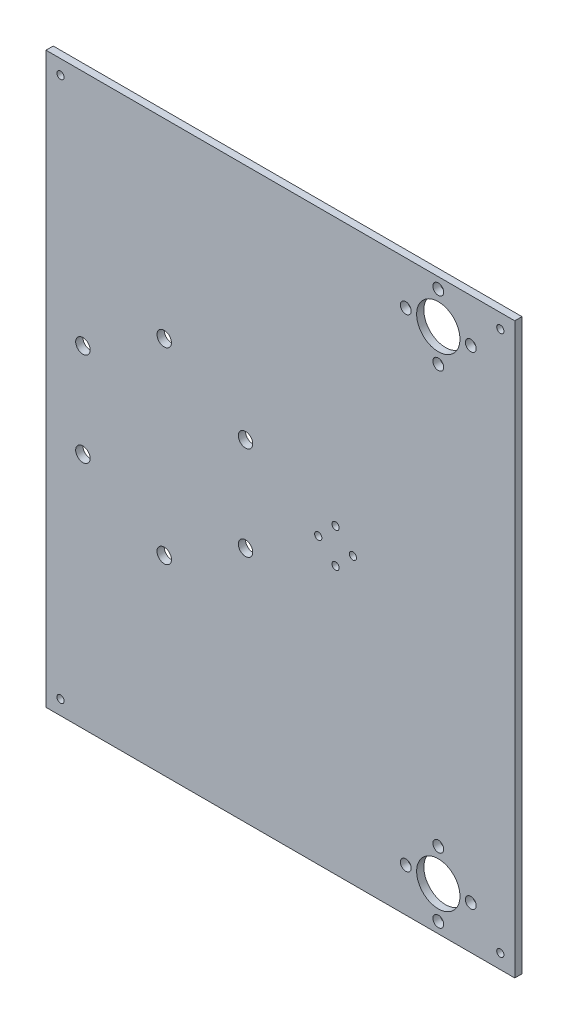
SolidWorks part; units mm, degrees
ref_plane "Front Plane" through (0, 0, 0) normal (0, 0, 1) x (1, 0, 0)
ref_plane "Top Plane" through (0, 0, 0) normal (0, 1, 0) x (1, 0, 0)
ref_plane "Right Plane" through (0, 0, 0) normal (1, 0, 0) x (0, 0, -1)
sketch "Sketch1" plane through (0, 0, 0) normal (0, 0, 1) x (1, 0, 0)
  line L1 (-162.25, 197) -> (162.25, 197)
  line L2 (-162.25, 197) -> (-162.25, -197)
  line L3 (-162.25, -197) -> (162.25, -197)
  line L4 (162.25, 197) -> (162.25, -197)
  line L5 (-162.25, 197) -> (162.25, -197) construction
  line L6 (-162.25, -197) -> (162.25, 197) construction
  point P0 (0, 0)
  dimension "D1" = 324.5
  dimension "D2" = 394
extrude "Boss-Extrude1" add sketch "Sketch1" along normal blind 5
sketch "Sketch2" plane through (0, 0, 5) normal (0, 0, 1) x (1, 0, 0)
  line L0 (162.25, 197) -> (-162.25, 197) construction
  line L1 (162.25, -197) -> (162.25, 197) construction
  line L2 (-162.25, -197) -> (162.25, -197) construction
  line L3 (-162.25, 197) -> (-162.25, -197) construction
  circle A0 centre (152.25, 187) radius 2.5
  circle A1 centre (-152.25, 187) radius 2.5
  circle A2 centre (-152.25, -187) radius 2.5
  circle A3 centre (152.25, -187) radius 2.5
  dimension "D1" = 5
  dimension "D2" = 5
  dimension "D3" = 5
  dimension "D4" = 5
  dimension "D5" = 10
  dimension "D6" = 10
  dimension "D7" = 10
  dimension "D8" = 10
  dimension "D9" = 10
  dimension "D10" = 10
  dimension "D11" = 10
  dimension "D12" = 10
extrude "Cut-Extrude1" cut sketch "Sketch2" against normal through all
sketch "Sketch4" plane through (0, 0, 0) normal (0, 0, -1) x (-1, 0, 0)
  circle A1 centre (80.4222, 65) radius 5
  circle A2 centre (136.7139, 32.5) radius 5
  circle A3 centre (136.7139, -32.5) radius 5
  circle A4 centre (80.4222, -65) radius 5
  circle A5 centre (24.1306, -32.5) radius 5
  circle A6 centre (24.1306, 32.5) radius 5
  point P16 (80.4222, 0)
  dimension "D2" = 10
  dimension "D4" = 6
extrude "Cut-Extrude3" cut sketch "Sketch4" against normal blind 5
sketch "Sketch5" plane through (0, 0, 5) normal (0, 0, 1) x (1, 0, 0)
  circle A1 centre (38.1924, 12) radius 2.5
  circle A2 centre (50.1924, 0) radius 2.5
  circle A3 centre (38.1924, -12) radius 2.5
  circle A4 centre (26.1924, 0) radius 2.5
  point P13 (38.1924, 0)
  dimension "D2" = 5
  dimension "D4" = 4
extrude "Cut-Extrude4" cut sketch "Sketch5" against normal blind 5
sketch "Sketch7" plane through (0, 0, 0) normal (0, 0, -1) x (-1, 0, 0)
  line L0 (-162.25, 197) -> (162.25, 197) construction
  line L1 (162.25, -197) -> (-162.25, -197) construction
  line L4 (162.25, 197) -> (162.25, -197) construction
  circle A0 centre (-109.31, 167) radius 15
  circle A1 centre (-109.31, -167) radius 15
  circle A2 centre (-109.31, 189.5) radius 3.75
  circle A10 centre (-109.31, -144.5) radius 3.75
  circle A17 centre (-86.81, -167) radius 3.75
  circle A18 centre (-109.31, -189.5) radius 3.75
  circle A19 centre (-131.81, -167) radius 3.75
  circle A20 centre (-86.81, 167) radius 3.75
  circle A21 centre (-109.31, 144.5) radius 3.75
  circle A22 centre (-131.81, 167) radius 3.75
  point P21 (-85.25, 167)
  point P24 (-96.215, -167)
  point P25 (-109.31, -167)
  point P30 (-85.25, -167)
  point P32 (-96.215, 167)
  point P34 (-109.31, 167)
  dimension "D1" = 30
  dimension "D2" = 30
  dimension "D7" = 7.5
  dimension "D10" = 22.5
  dimension "D9" = 7.5
  dimension "D3" = 30
  dimension "D4" = 30
  dimension "D5" = 271.56
  dimension "D6" = 271.56
  dimension "D8" = 22.5
  dimension "D11" = 4
  dimension "D12" = 4
extrude "Cut-Extrude6" cut sketch "Sketch7" against normal through all
